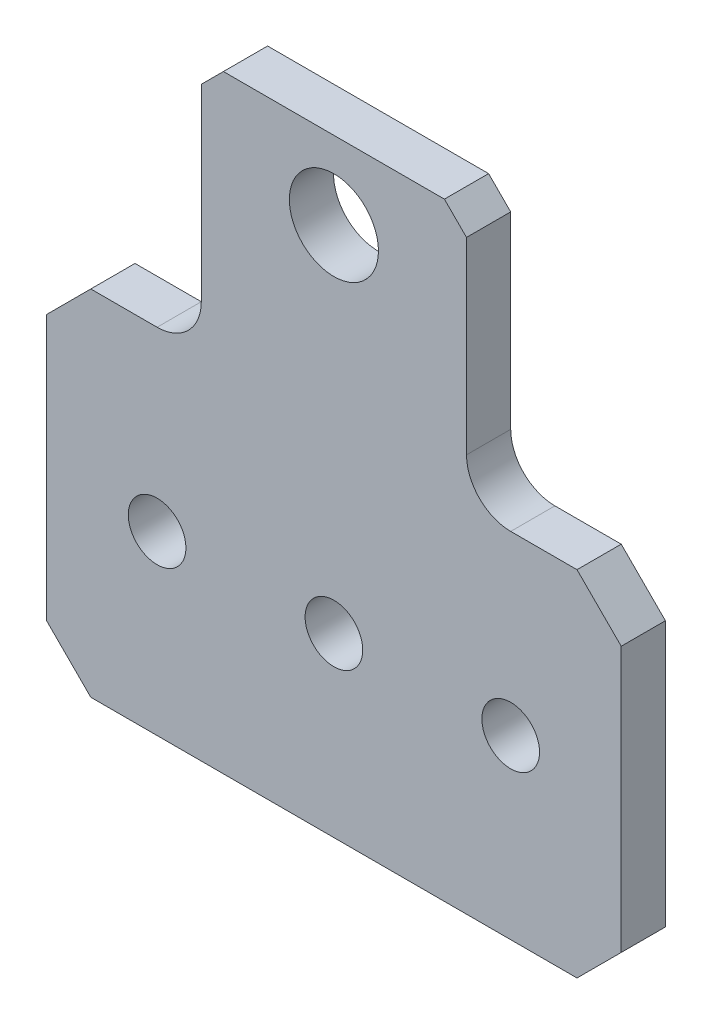
SolidWorks part; units mm, degrees
material "6061-T6 (SS)"
ref_plane "Front Plane" through (0, 0, 0) normal (0, 0, 1) x (1, 0, 0)
ref_plane "Top Plane" through (0, 0, 0) normal (0, 1, 0) x (1, 0, 0)
ref_plane "Right Plane" through (0, 0, 0) normal (1, 0, 0) x (0, 0, -1)
ref_plane "Plane1" through (0, 0, 0) normal (0, 0, -1) x (-1, 0, 0)
sketch "Sketch1" plane through (0, 0, 0) normal (0, 0, -1) x (-1, 0, 0)
  line L0 (-17.4625, -15.494) -> (-20.6375, -18.669)
  line L1 (-20.6375, -18.669) -> (-20.6375, -37.719)
  line L2 (-20.6375, -37.719) -> (-17.4625, -40.894)
  line L3 (-17.4625, -40.894) -> (17.4625, -40.894)
  line L4 (17.4625, -40.894) -> (20.6375, -37.719)
  line L5 (20.6375, -37.719) -> (20.6375, -18.669)
  line L6 (20.6375, -18.669) -> (17.4625, -15.494)
  line L7 (17.4625, -15.494) -> (12.7, -15.494)
  line L8 (9.525, -12.319) -> (9.525, 1.2065)
  line L9 (9.525, 1.2065) -> (7.9375, 2.794)
  line L10 (7.9375, 2.794) -> (9.525, 4.3815)
  line L11 (9.525, 4.3815) -> (9.525, 37.719)
  line L12 (9.525, 37.719) -> (6.35, 40.894)
  line L13 (6.35, 40.894) -> (-6.35, 40.894)
  line L14 (-6.35, 40.894) -> (-9.525, 37.719)
  line L15 (-9.525, 37.719) -> (-9.525, 4.3815)
  line L16 (-9.525, 4.3815) -> (-7.9375, 2.794)
  line L17 (-7.9375, 2.794) -> (-9.525, 1.2065)
  line L18 (-9.525, 1.2065) -> (-9.525, -12.319)
  line L19 (-12.7, -15.494) -> (-17.4625, -15.494)
  arc A0 (12.7, -15.494) -> (9.525, -12.319) centre (12.7, -12.319) cw
  arc A1 (-9.525, -12.319) -> (-12.7, -15.494) centre (-12.7, -12.319) cw
  circle A2 centre (0, 35.306) radius 3.2004
  circle A3 centre (0, -2.794) radius 3.2004
  circle A4 centre (12.7, -28.194) radius 2.0701
  circle A5 centre (-12.7, -28.194) radius 2.0701
  circle A6 centre (0, -28.194) radius 2.0701
extrude "Boss-Extrude1" add sketch "Sketch1" against normal blind 3.175
sketch "Sketch2" plane through (0, 0, 0) normal (0, 0, 1) x (1, 0, 0)
  line L1 (-51.1795, 55.7212) -> (41.9721, 55.7212)
  line L2 (-51.1795, 55.7212) -> (-51.1795, 2.794)
  line L3 (-51.1795, 2.794) -> (41.9721, 2.794)
  line L4 (41.9721, 55.7212) -> (41.9721, 2.794)
extrude "Cut-Extrude1" cut sketch "Sketch2" along normal through all
